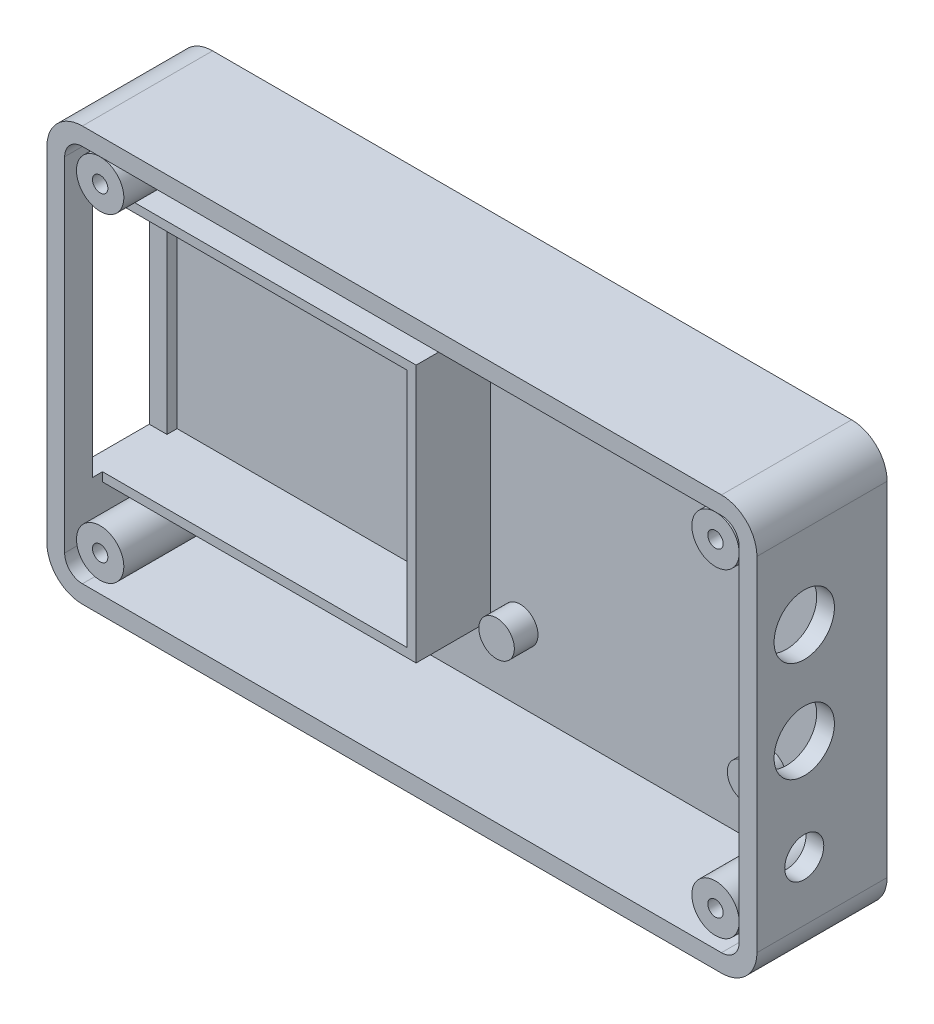
SolidWorks part; units mm, degrees
ref_plane "Front Plane" through (0, 0, 0) normal (0, 0, 1) x (1, 0, 0)
ref_plane "Top Plane" through (0, 0, 0) normal (0, 1, 0) x (1, 0, 0)
ref_plane "Right Plane" through (0, 0, 0) normal (1, 0, 0) x (0, 0, -1)
sketch "Sketch1" plane through (0, 0, 0) normal (0, 0, 1) x (1, 0, 0)
  line L1 (-60, 35) -> (60, 35)
  line L2 (-60, 35) -> (-60, -35)
  line L3 (-60, -35) -> (60, -35)
  line L4 (60, 35) -> (60, -35)
  point P4 (0, 35)
  point P6 (60, 0)
  dimension "D1" = 120
  dimension "D2" = 70
extrude "Boss-Extrude1" add sketch "Sketch1" along normal blind 22
fillet "Fillet1" radius 6 4 edges at (-60, -35, 11) (60, -35, 11) (-60, 35, 11) (60, 35, 11)
shell "Shell1" thickness 3
sketch "Sketch2" plane through (0, 0, 3) normal (0, 0, 1) x (1, 0, 0)
  line L0 (0, -12.1) -> (0, 12.1) construction
  line L1 (12.1, 0) -> (-12.1, 0) construction
  circle A0 centre (-52, -27) radius 4
  circle A4 centre (52, -27) radius 4
  circle A5 centre (52, 27) radius 4
  circle A6 centre (-52, 27) radius 4
  dimension "D1" = 8
  dimension "D2" = 52
  dimension "D3" = 27
extrude "Boss-Extrude2" add sketch "Sketch2" along normal blind 18
sketch "Sketch4" plane through (0, 0, 21) normal (0, 0, 1) x (1, 0, 0)
  line L0 (12.1, 0) -> (-12.1, 0) construction
  line L1 (0, -12.1) -> (0, 12.1) construction
  circle A0 centre (-52, 27) radius 1.3
  circle A1 centre (-52, 27) radius 4 construction
  circle A2 centre (-52, -27) radius 1.3
  circle A3 centre (52, -27) radius 1.3
  circle A4 centre (52, 27) radius 1.3
  dimension "D1" = 2.6
extrude "Cut-Extrude1" cut sketch "Sketch4" against normal blind 4
sketch "Sketch5" plane through (0, 0, 3) normal (0, 0, -1) x (-1, 0, 0)
  line L0 (12.1, 0) -> (-12.1, 0) construction
  line L1 (5.5, 21.8) -> (57, 21.8)
  line L2 (5.5, 21.8) -> (5.5, 20.3)
  line L3 (5.5, 20.3) -> (57, 20.3)
  line L4 (57, 21.8) -> (57, 20.3)
  line L5 (57, -21.8) -> (57, -20.3)
  line L6 (5.5, -20.3) -> (57, -20.3)
  line L8 (5.5, -21.8) -> (57, -21.8)
  line L10 (4, 21.8) -> (5.5, 21.8)
  line L11 (4, 21.8) -> (4, -21.8)
  line L12 (4, -21.8) -> (5.5, -21.8)
  line L13 (5.5, 21.8) -> (5.5, -21.8)
  point P4 (5.5, 21.05)
  point P7 (31.25, 20.3)
  point P19 (4.75, 21.8)
  point P20 (4, 0)
  line M32 (57, 29) -> (57, -29)
  dimension "D1" = 51.5
  dimension "D2" = 1.5
  dimension "D3" = 21.05
  dimension "D4" = 31.25
  dimension "D5" = 1.5
  dimension "D6" = 43.6
  dimension "D7" = 4.75
extrude "Boss-Extrude3" add sketch "Sketch5" against normal blind 12.6 contours L2 L13 L12 L11 L10 | L13 L6 L8 M32
sketch "Sketch6" plane through (-60, 0, 0) normal (1, 0, 0) x (0, 0, -1)
  line L1 (-17.3, 20.3) -> (-4.7, 20.3)
  line L2 (-17.3, 20.3) -> (-17.3, -20.3)
  line L3 (-17.3, -20.3) -> (-4.7, -20.3)
  line L4 (-4.7, 20.3) -> (-4.7, -20.3)
  line L5 (-22, 35) -> (0, 35) construction
  point P6 (-4.7, 0)
  point P7 (-11, 35)
  point P11 (-11, 20.3)
  dimension "D1" = 40.6
  dimension "D2" = 12.6
extrude "Cut-Extrude2" cut sketch "Sketch6" along normal up to next
sketch "Sketch8" plane through (60, 0, 0) normal (-1, 0, 0) x (0, 0, 1)
  circle A0 centre (14, 15) radius 5.1
  circle A1 centre (14, -2) radius 5.1
  circle A2 centre (14, -19) radius 3.3
  dimension "D1" = 10.2
  dimension "D2" = 6.6
  dimension "D3" = 14
  dimension "D4" = 19
  dimension "D5" = 2
  dimension "D6" = 15
extrude "Cut-Extrude3" cut sketch "Sketch8" along normal up to next
sketch "Sketch9" plane through (0, 0, 3) normal (0, 0, 1) x (1, 0, 0)
  line L0 (12.1, 0) -> (-12.1, 0) construction
  circle A0 centre (43, 20) radius 3
  circle A1 centre (1, 20) radius 3
  circle A4 centre (1, -20) radius 3
  circle A5 centre (43, -20) radius 3
  dimension "D1" = 6
  dimension "D2" = 43
  dimension "D3" = 20
  dimension "D4" = 1
extrude "Boss-Extrude4" add sketch "Sketch9" along normal blind 4
